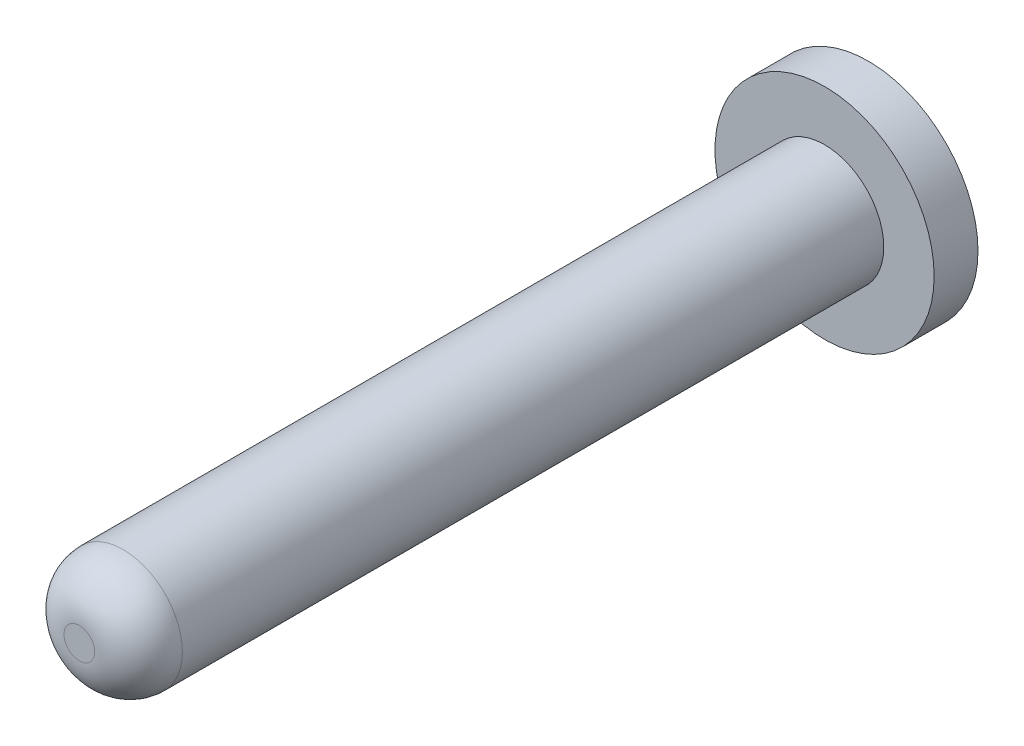
SolidWorks part; units mm, degrees
ref_plane "前视基准面" through (0, 0, 0) normal (0, 0, 1) x (1, 0, 0)
ref_plane "上视基准面" through (0, 0, 0) normal (0, 1, 0) x (1, 0, 0)
ref_plane "右视基准面" through (0, 0, 0) normal (1, 0, 0) x (0, 0, -1)
sketch "草图1" plane through (0, 0, 0) normal (0, 0, 1) x (1, 0, 0)
  circle A0 centre (0, 0) radius 2.5
  dimension "D1" = 5
extrude "凸台-拉伸1" add sketch "草图1" along normal blind 1
sketch "草图2" plane through (0, 0, 1) normal (0, 0, 1) x (1, 0, 0)
  circle A0 centre (0, 0) radius 1.35
extrude "凸台-拉伸2" add sketch "草图2" along normal blind 17
fillet "圆角1" radius 1 1 edges at (1.35, 0, 18)
